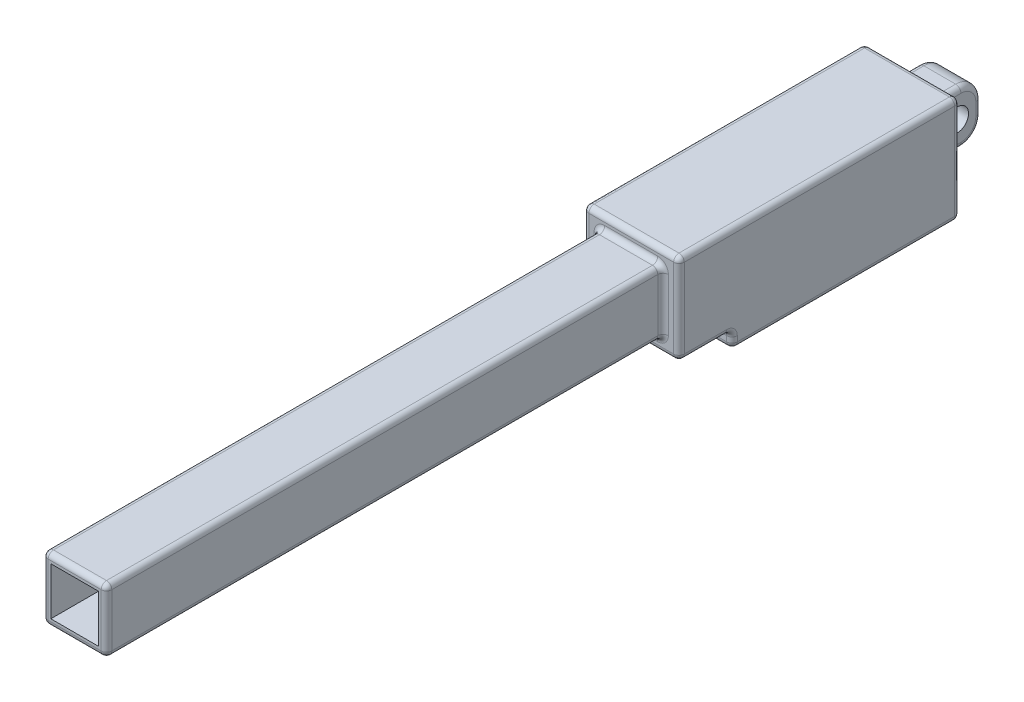
SolidWorks part; units mm, degrees
ref_plane "Plan de face" through (0, 0, 0) normal (0, 0, 1) x (1, 0, 0)
ref_plane "Plan de dessus" through (0, 0, 0) normal (0, 1, 0) x (1, 0, 0)
ref_plane "Plan de droite" through (0, 0, 0) normal (1, 0, 0) x (0, 0, -1)
sketch "Esquisse1" plane through (0, 0, 0) normal (0, 0, 1) x (1, 0, 0)
  line L1 (0, 0) -> (18, 0)
  line L2 (0, 0) -> (0, 20)
  line L3 (0, 20) -> (18, 20)
  line L4 (18, 0) -> (18, 20)
  dimension "D1" = 18
  dimension "D2" = 20
extrude "Extrusion1" add sketch "Esquisse1" along normal blind 43
sketch "Esquisse4" plane through (0, 0, 43) normal (0, 0, 1) x (1, 0, 0)
  line L0 (9.9, 0) -> (-9.9, 0) construction
  line L1 (18, 20) -> (0, 20)
  line L2 (18, 20) -> (18, 3)
  line L3 (18, 3) -> (0, 3)
  line L4 (0, 20) -> (0, 3)
  line L5 (18, 0) -> (18, 20) construction
  dimension "D1" = 17
  dimension "D2" = 3
  dimension "D3" = 18
  dimension "D4" = 18
extrude "Extrusion3" add sketch "Esquisse4" along normal blind 10
sketch "Esquisse7" plane through (0, 0, 0) normal (0, 0, -1) x (-1, 0, 0)
  line L1 (-13, 16.5) -> (-5, 16.5)
  line L2 (-13, 16.5) -> (-13, 6.5)
  line L3 (-13, 6.5) -> (-5, 6.5)
  line L4 (-5, 16.5) -> (-5, 6.5)
  line L5 (-18, 20) -> (0, 20) construction
  line L6 (0, 20) -> (0, 3) construction
  dimension "D1" = 8
  dimension "D2" = 10
  dimension "D3" = 3.5
  dimension "D4" = 5
extrude "Extrusion4" add sketch "Esquisse7" along normal blind 9
fillet "Congé5" radius 3.8 2 edges at (9, 6.5, -9) (9, 16.5, -9)
fillet "Congé6" radius 1 32 edges at (13, 6.5, -2.6) (13, 7.613, -7.887) (13, 11.5, -9) (13, 16.5, -2.6) (5, 6.5, -2.6) (5, 7.613, -7.887) (5, 11.5, -9) (5, 11.5, 0) (9, 16.5, 0) (13, 11.5, 0) (9, 6.5, 0) (18, 10, 0) (9, 20, 0) (9, 3, 53) (9, 20, 53) (18, 11.5, 53) (9, 0, 43) (18, 0, 21.5) (9, 0, 0) (0, 20, 26.5) (0, 11.5, 53) (0, 0, 21.5) (0, 10, 0) (13, 15.387, -7.887) (5, 15.387, -7.887) (5, 16.5, -2.6) (18, 20, 26.5)
sketch "Esquisse8" plane through (5, 0, 0) normal (-1, 0, 0) x (0, 0, 1)
  line L0 (0, -9.9001) -> (0, 9.9001) construction
  line L1 (-5.2, 16.5) -> (-1, 16.5) construction
  circle A0 centre (-4.5, 11.5) radius 2.125
  dimension "D1" = 4.5
  dimension "D2" = 5
extrude "Enlèv. mat.-Extru.1" cut sketch "Esquisse8" against normal through all
sketch "Esquisse6" plane through (0, 0, 53) normal (0, 0, 1) x (1, 0, 0)
  line L0 (0, 3) -> (18, 3) construction
  line L1 (15, 5.5) -> (3, 5.5)
  line L2 (15, 5.5) -> (15, 17.5)
  line L3 (15, 17.5) -> (3, 17.5)
  line L4 (3, 5.5) -> (3, 17.5)
  line L6 (18, 3) -> (18, 20) construction
  dimension "D1" = 12
  dimension "D2" = 2.5
  dimension "D3" = 3
  dimension "D4" = 12
extrude "Extrusion5" add sketch "Esquisse6" along normal blind 105
fillet "Congé7" radius 1 12 edges at (9, 17.5, 53) (3, 17.5, 105.5) (3, 11.5, 53) (3, 11.5, 158) (9, 17.5, 158) (15, 11.5, 158) (15, 17.5, 105.5) (15, 11.5, 53) (3, 5.5, 105.5) (9, 5.5, 158) (15, 5.5, 105.5) (9, 5.5, 53)
sketch "Esquisse9" plane through (0, 0, 158) normal (0, 0, 1) x (1, 0, 0)
  line L0 (3, 6.5) -> (3, 16.5) construction
  line L1 (13.5, 7) -> (4.5, 7)
  line L2 (13.5, 7) -> (13.5, 16)
  line L3 (13.5, 16) -> (4.5, 16)
  line L4 (4.5, 7) -> (4.5, 16)
  line L5 (14, 5.5) -> (4, 5.5) construction
  dimension "D1" = 9
  dimension "D2" = 1.5
  dimension "D3" = 9
  dimension "D4" = 1.5
extrude "Enlèv. mat.-Extru.2" cut sketch "Esquisse9" against normal blind 106
